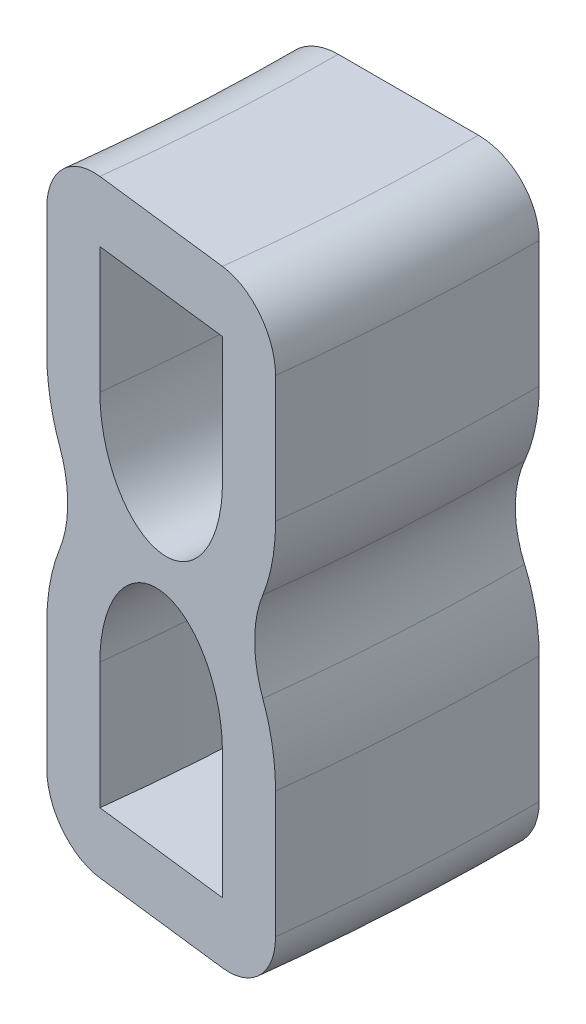
SolidWorks part; units mm, degrees
ref_plane "Front Plane" through (0, 0, 0) normal (0, 0, 1) x (1, 0, 0)
ref_plane "Top Plane" through (0, 0, 0) normal (0, 1, 0) x (1, 0, 0)
ref_plane "Right Plane" through (0, 0, 0) normal (1, 0, 0) x (0, 0, -1)
sketch "DualPropShadow" plane through (0, 0, 0) normal (0, 0, 1) x (1, 0, 0)
  line L1 (-1.2, -1.2) -> (1.2, -1.2)
  line L2 (-1.2, -1.2) -> (-1.2, 1.2)
  line L3 (-1.2, 1.2) -> (1.2, 1.2) construction
  line L4 (1.2, -1.2) -> (1.2, 1.2)
  line L5 (-1.2, -1.2) -> (1.2, 1.2) construction
  line L6 (-1.2, 1.2) -> (1.2, -1.2) construction
  line L8 (0, 1.2) -> (0, 3.2) construction
  line L9 (-1000, 3.7) -> (49000, 3.7) construction
  line L10 (0, 6.2) -> (0, 4.2) construction
  line L11 (-1.2, 6.2) -> (1.2, 8.6) construction
  line L12 (-1.2, 8.6) -> (1.2, 6.2) construction
  line L18 (0, 3.2) -> (-1.2, 1.2)
  line L19 (0, 3.2) -> (1.2, 1.2)
  line L20 (-1.2, 6.2) -> (1.2, 6.2) construction
  line L21 (0, 4.2) -> (1.2, 6.2)
  line L22 (0, 4.2) -> (-1.2, 6.2)
  line L23 (1.2, 8.6) -> (1.2, 6.2)
  line L24 (-1.2, 8.6) -> (-1.2, 6.2)
  line L25 (-1.2, 8.6) -> (1.2, 8.6)
  point P0 (0, 0)
  point P6 (1.2, 0)
  point P7 (0, 3.2)
  point P17 (0, 4.2)
  point P19 (0, 7.4)
  point P20 (0, 6.0465)
  point P21 (0, 0)
  point P22 (0, 3.2)
  point P23 (0, 0)
  dimension "D1" = 2.4
  dimension "D3" = 2.4
  dimension "D2" = 4.4
  dimension "D4" = 1
sketch "Sketch2" plane through (0, 0, 0) normal (0, 0, 1) x (1, 0, 0)
  line L0 (-2.4878, 4.6595) -> (-2.0708, 3.7) construction
  line L1 (-1.2732, 5.0632) -> (-0.6807, 3.7) construction
  line L2 (-1.5, -2.8) -> (1.5, -2.8)
  line L3 (-1.5, -1.5) -> (1.5, -1.5)
  line L4 (-1.5, -1.5) -> (-1.5, 1.2)
  line L5 (-2.8, -1.5) -> (-2.8, 1.2)
  line L6 (1.5, -1.5) -> (1.5, 1.2)
  line L7 (2.8, -1.5) -> (2.8, 1.2)
  line L8 (2.8, 8.9) -> (2.8, 6.2)
  line L9 (1.5, 8.9) -> (1.5, 6.2)
  line L20 (1.2, -1.2) -> (1.2, 1.2) construction
  line L22 (-1.2, -1.2) -> (1.2, -1.2) construction
  line L23 (-1.2, -1.2) -> (-1.2, 1.2) construction
  line L24 (0, 3.2) -> (-1.2, 1.2) construction
  line L25 (0, 3.2) -> (1.2, 1.2) construction
  line L26 (1.2, 8.6) -> (1.2, 6.2) construction
  line L27 (0, 4.2) -> (1.2, 6.2) construction
  line L29 (0, 4.2) -> (-1.2, 6.2) construction
  line L30 (-1.2, 8.6) -> (-1.2, 6.2) construction
  line L32 (-1.2, 8.6) -> (1.2, 8.6) construction
  line L33 (1.2, -1.2) -> (1.2, 1.2) construction
  line L34 (-1.2, -1.2) -> (1.2, -1.2) construction
  line L35 (-1.2, -1.2) -> (-1.2, 1.2) construction
  line L36 (0, 3.2) -> (-1.2, 1.2) construction
  line L37 (0, 3.2) -> (1.2, 1.2) construction
  line L38 (1.2, 8.6) -> (1.2, 6.2) construction
  line L39 (0, 4.2) -> (1.2, 6.2) construction
  line L40 (0, 4.2) -> (-1.2, 6.2) construction
  line L41 (-1.2, 8.6) -> (-1.2, 6.2) construction
  line L42 (-1.2, 8.6) -> (1.2, 8.6) construction
  line L43 (0, 8.6) -> (0, -1.2) construction
  line L44 (0, 3.7) -> (-1.2, 3.7) construction
  line L45 (-1.5, 8.9) -> (1.5, 8.9)
  line L46 (-1.5, 10.2) -> (1.5, 10.2)
  line L47 (-1.5, 8.9) -> (-1.5, 6.2)
  line L48 (-2.8, 8.9) -> (-2.8, 6.2)
  line L49 (-1.2, 8.6) -> (-1.2, 8.9) construction
  line L50 (-1.2, 8.6) -> (-1.5, 8.6) construction
  arc A1 (-1.5, 10.2) -> (-2.8, 8.9) centre (-1.5, 8.9) ccw
  arc A2 (-2.4878, 2.7405) -> (-2.4878, 4.6595) centre (-4.6954, 3.7) ccw
  arc A3 (-1.5, -2.8) -> (-2.8, -1.5) centre (-1.5, -1.5) cw
  arc A4 (1.5, 10.2) -> (2.8, 8.9) centre (1.5, 8.9) cw
  arc A5 (1.5, -2.8) -> (2.8, -1.5) centre (1.5, -1.5) ccw
  arc A6 (2.4878, 2.7405) -> (2.4878, 4.6595) centre (4.6954, 3.7) cw
  circle A8 centre (-1.3883, 3.7) radius 0.9 construction
  ellipse E0 centre (0, 6.2) end of major axis (0, 4.05) minor radius 1.5 (-1.5, 6.2) -> (1.5, 6.2) ccw
  ellipse E1 centre (-0.3255, 6.2) end of major axis (-0.3255, 3.0317) minor radius 2.4745 (-2.4878, 4.6595) -> (-2.8, 6.2) cw
  ellipse E2 centre (0, 1.2) end of major axis (0, 3.35) minor radius 1.5 (-1.5, 1.2) -> (1.5, 1.2) cw
  ellipse E3 centre (-0.3255, 1.2) end of major axis (-0.3255, -1.9683) minor radius 2.4745 (-2.4878, 2.7405) -> (-2.8, 1.2) ccw
  ellipse E4 centre (0.3255, 6.2) end of major axis (0.3255, 3.0317) minor radius 2.4745 (2.4878, 4.6595) -> (2.8, 6.2) ccw
  ellipse E5 centre (0.3255, 1.2) end of major axis (0.3255, -1.9683) minor radius 2.4745 (2.4878, 2.7405) -> (2.8, 1.2) cw
  point P19 (0, 8.9)
  point P43 (0, 0)
  point P44 (-2.1041, 6.2)
  point P45 (0, 0)
  point P59 (0, -2.8)
  point P84 (0, -1.5)
  point P91 (0, 10.2)
  dimension "D3" = 0.15
  dimension "D4" = 1.8
  dimension "D1" = 1.3
  dimension "D2" = 0.3
sketch "Sketch12" plane through (0, 0, 0) normal (0, 1, 0) x (1, 0, 0)
  arc A0 (0, 0) -> (-0.2976, -4.9911) centre (-42, 0) cw
  point P3 (0, 0)
  point P4 (-39.9265, -13.0336)
  point P6 (0, 0)
  point P7 (-42, 0)
  point P8 (0, 0)
  point P9 (-42, 0)
  dimension "D1" = 42
  dimension "D2" = 5
sweep "Sweep2" add profiles "Sketch2" path "Sketch12"
equation "\"prop_height\"= 4.4mm"
equation "\"prop_th\"= 2.4mm"
equation "\"prop_indent_height\"= 2.4mm"
equation "\"prop_radius\"= 42mm"
equation "\"D1@DualPropShadow\" = \"prop_indent_height\""
equation "\"D3@DualPropShadow\" = \"prop_th\""
equation "\"D1@Sketch12\"=\"prop_radius\""
equation "\"D2@DualPropShadow\"=\"prop_height\""
